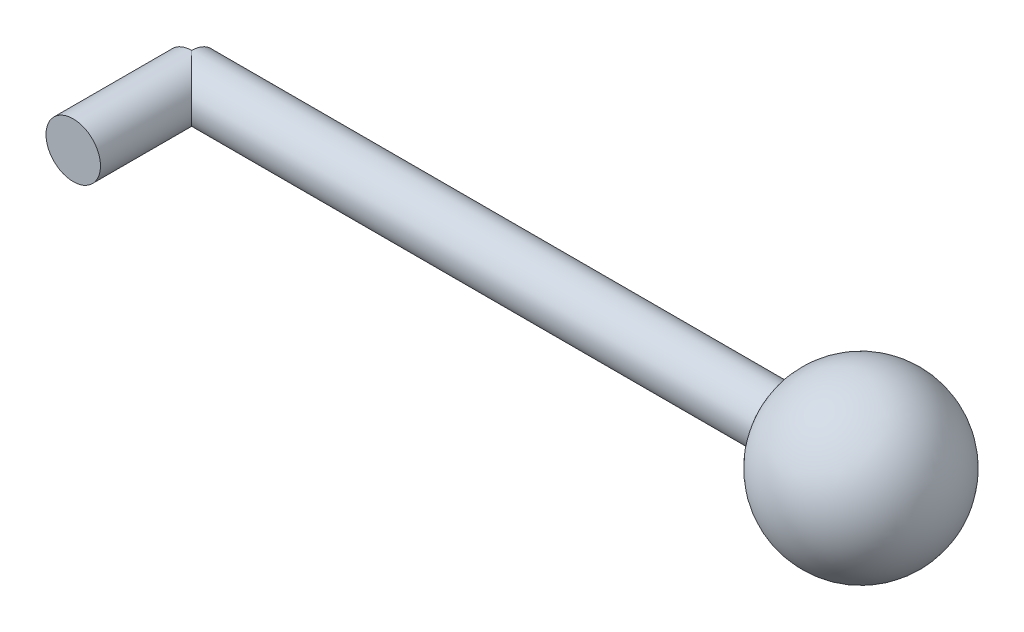
SolidWorks part; units mm, degrees
material "Legs"
ref_plane "Front Plane" through (0, 0, 0) normal (0, 0, 1) x (1, 0, 0)
ref_plane "Top Plane" through (0, 0, 0) normal (0, 1, 0) x (1, 0, 0)
ref_plane "Right Plane" through (0, 0, 0) normal (1, 0, 0) x (0, 0, -1)
sketch "Sketch1" plane through (0, 0, 0) normal (1, 0, 0) x (0, 0, -1)
  circle A0 centre (0, 0) radius 23
  dimension "D1" = 46
extrude "Length" add sketch "Sketch1" along normal blind 565
sketch "Sketch2" plane through (0, 0, 0) normal (0, 0, 1) x (1, 0, 0)
  circle A0 centre (0, 0) radius 23
  dimension "D1" = 46
extrude "Hip joint" add sketch "Sketch2" along normal blind 100
ref_axis "Axis2" through (565, 0, 0) along (-1, 0, 0)
ref_point "Point1"
sketch "Sketch10" plane through (0, 0, 0) normal (0, 0, 1) x (1, 0, 0)
  line L0 (495, 0) -> (635, 0)
  arc A0 (495, 0) -> (635, 0) centre (565, 0) ccw
revolve "Revolve23" add sketch "Sketch10" angle 360 about axis through (565, 0, 0) along (-1, 0, 0)
